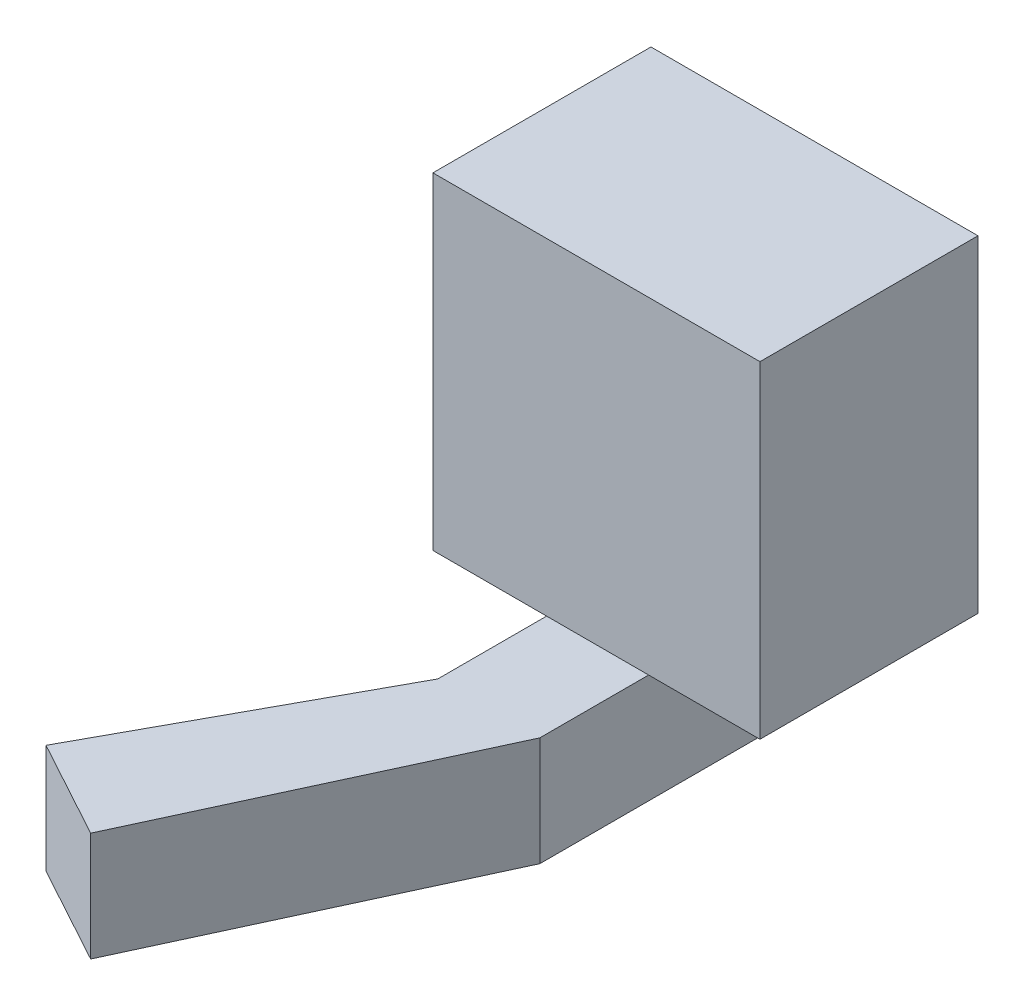
SolidWorks part; units mm, degrees
ref_plane "Front Plane" through (0, 0, 0) normal (0, 0, 1) x (1, 0, 0)
ref_plane "Top Plane" through (0, 0, 0) normal (0, 1, 0) x (1, 0, 0)
ref_plane "Right Plane" through (0, 0, 0) normal (1, 0, 0) x (0, 0, -1)
sketch "Sketch1" plane through (0, 0, 0) normal (0, 0, 1) x (1, 0, 0)
  line L1 (0, 0) -> (30, 0)
  line L2 (0, 0) -> (0, 30)
  line L3 (0, 30) -> (30, 30)
  line L4 (30, 0) -> (30, 30)
  dimension "D1" = 30
  dimension "D2" = 30
extrude "Boss-Extrude1" add sketch "Sketch1" along normal blind 20
sketch "Sketch2" plane through (0, 0, 0) normal (0, -1, 0) x (1, 0, 0)
  line L0 (0, 20) -> (30, 20) construction
  line L1 (10.4279, 5.6905) -> (19.7883, 5.6905)
  line L2 (10.4279, 5.6905) -> (10.4279, 20)
  line L3 (10.4279, 20) -> (19.7883, 20)
  line L4 (19.7883, 5.6905) -> (19.7883, 20)
extrude "Boss-Extrude2" add sketch "Sketch2" along normal blind 10
sketch "Sketch3" plane through (0, -10, 0) normal (0, -1, 0) x (1, 0, 0)
  line L0 (10.4279, 29.9801) -> (-2.2681, 53.2255)
  line L1 (10.4279, 20) -> (19.7883, 20)
  line L2 (10.4279, 20) -> (10.4279, 29.9801)
  line L4 (19.7883, 20) -> (19.7883, 29.9801)
  line L5 (-2.2681, 53.2255) -> (6.7597, 58.1562)
  line L6 (6.7597, 58.1562) -> (19.7883, 29.9801)
extrude "Boss-Extrude3" add sketch "Sketch3" against normal blind 10
